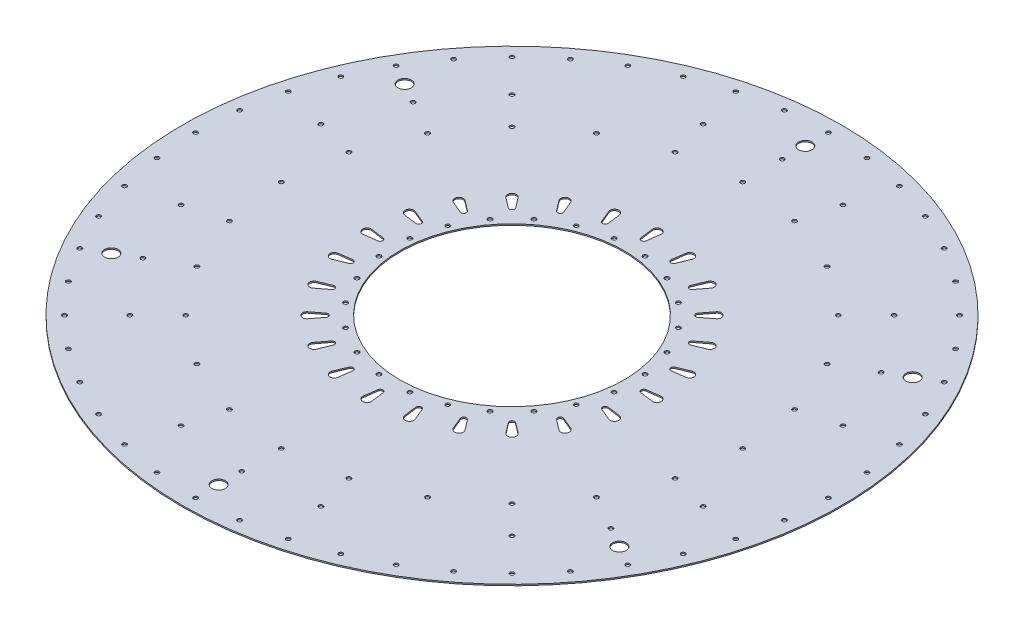
SolidWorks part; units mm, degrees
ref_plane "Front Plane" through (0, 0, 0) normal (0, 0, 1) x (1, 0, 0)
ref_plane "Top Plane" through (0, 0, 0) normal (0, 1, 0) x (1, 0, 0)
ref_plane "Right Plane" through (0, 0, 0) normal (1, 0, 0) x (0, 0, -1)
sketch "Sketch2" plane through (0, 0, 0) normal (0, 1, 0) x (1, 0, 0)
  line L0 (0, 0) -> (0, 231.6511) construction
  line L1 (-5.5, 109.8624) -> (-5, 99.8749) construction
  line L2 (5.5, 109.8624) -> (5, 99.8749) construction
  line L3 (-4.1887, 108.6693) -> (-3.8137, 101.1782) construction
  line L4 (4.1887, 108.6693) -> (3.8137, 101.1782) construction
  line L5 (24.0797, 106.0506) -> (22.5031, 98.7176) construction
  line L6 (32.1717, 103.8824) -> (29.8706, 96.7435) construction
  line L7 (50.7071, 96.2047) -> (47.2863, 89.5297) construction
  line L8 (57.9622, 92.016) -> (53.8918, 85.716) construction
  line L9 (73.8789, 79.8027) -> (68.8471, 74.2404) construction
  line L10 (79.8027, 73.8789) -> (74.2404, 68.8471) construction
  line L11 (92.016, 57.9622) -> (85.716, 53.8918) construction
  line L12 (96.2047, 50.7071) -> (89.5297, 47.2863) construction
  line L13 (103.8824, 32.1717) -> (96.7435, 29.8706) construction
  line L14 (106.0506, 24.0797) -> (98.7176, 22.5031) construction
  line L15 (108.6693, 4.1887) -> (101.1782, 3.8137) construction
  line L16 (108.6693, -4.1887) -> (101.1782, -3.8137) construction
  line L17 (106.0506, -24.0797) -> (98.7176, -22.5031) construction
  line L18 (103.8824, -32.1717) -> (96.7435, -29.8706) construction
  line L19 (96.2047, -50.7071) -> (89.5297, -47.2863) construction
  line L20 (92.016, -57.9622) -> (85.716, -53.8918) construction
  line L21 (79.8027, -73.8789) -> (74.2404, -68.8471) construction
  line L22 (73.8789, -79.8027) -> (68.8471, -74.2404) construction
  line L23 (57.9622, -92.016) -> (53.8918, -85.716) construction
  line L24 (50.7071, -96.2047) -> (47.2863, -89.5297) construction
  line L25 (32.1717, -103.8824) -> (29.8706, -96.7435) construction
  line L26 (24.0797, -106.0506) -> (22.5031, -98.7176) construction
  line L27 (4.1887, -108.6693) -> (3.8137, -101.1782) construction
  line L28 (-4.1887, -108.6693) -> (-3.8137, -101.1782) construction
  line L29 (-24.0797, -106.0506) -> (-22.5031, -98.7176) construction
  line L30 (-32.1717, -103.8824) -> (-29.8706, -96.7435) construction
  line L31 (-50.7071, -96.2047) -> (-47.2863, -89.5297) construction
  line L32 (-57.9622, -92.016) -> (-53.8918, -85.716) construction
  line L33 (-73.8789, -79.8027) -> (-68.8471, -74.2404) construction
  line L34 (-79.8027, -73.8789) -> (-74.2404, -68.8471) construction
  line L35 (-92.016, -57.9622) -> (-85.716, -53.8918) construction
  line L36 (-96.2047, -50.7071) -> (-89.5297, -47.2863) construction
  line L37 (-103.8824, -32.1717) -> (-96.7435, -29.8706) construction
  line L38 (-106.0506, -24.0797) -> (-98.7176, -22.5031) construction
  line L39 (-108.6693, -4.1887) -> (-101.1782, -3.8137) construction
  line L40 (-108.6693, 4.1887) -> (-101.1782, 3.8137) construction
  line L41 (-106.0506, 24.0797) -> (-98.7176, 22.5031) construction
  line L42 (-103.8824, 32.1717) -> (-96.7435, 29.8706) construction
  line L43 (-96.2047, 50.7071) -> (-89.5297, 47.2863) construction
  line L44 (-92.016, 57.9622) -> (-85.716, 53.8918) construction
  line L45 (-79.8027, 73.8789) -> (-74.2404, 68.8471) construction
  line L46 (-73.8789, 79.8027) -> (-68.8471, 74.2404) construction
  line L47 (-57.9622, 92.016) -> (-53.8918, 85.716) construction
  line L48 (-50.7071, 96.2047) -> (-47.2863, 89.5297) construction
  line L49 (-32.1717, 103.8824) -> (-29.8706, 96.7435) construction
  line L50 (-24.0797, 106.0506) -> (-22.5031, 98.7176) construction
  line L51 (0, 0) -> (192.6907, 111.25) construction
  line L52 (3.277, 109.5686) -> (1.9829, 99.7389)
  line L53 (-3.277, 109.5686) -> (-1.9829, 99.7389)
  line L54 (31.5238, 104.987) -> (27.7297, 95.8272)
  line L55 (25.1931, 106.6833) -> (23.899, 96.8536)
  line L56 (57.6222, 93.2507) -> (51.5867, 85.385)
  line L57 (51.9463, 96.5277) -> (48.1522, 87.3679)
  line L58 (79.7939, 75.1595) -> (71.9282, 69.124)
  line L59 (75.1595, 79.7939) -> (69.124, 71.9282)
  line L60 (96.5277, 51.9463) -> (87.3679, 48.1522)
  line L61 (93.2507, 57.6222) -> (85.385, 51.5867)
  line L62 (106.6833, 25.1931) -> (96.8536, 23.899)
  line L63 (104.987, 31.5238) -> (95.8272, 27.7297)
  line L64 (109.5686, -3.277) -> (99.7389, -1.9829)
  line L65 (109.5686, 3.277) -> (99.7389, 1.9829)
  line L66 (104.987, -31.5238) -> (95.8272, -27.7297)
  line L67 (106.6833, -25.1931) -> (96.8536, -23.899)
  line L68 (93.2507, -57.6222) -> (85.385, -51.5867)
  line L69 (96.5277, -51.9463) -> (87.3679, -48.1522)
  line L70 (75.1595, -79.7939) -> (69.124, -71.9282)
  line L71 (79.7939, -75.1595) -> (71.9282, -69.124)
  line L72 (51.9463, -96.5277) -> (48.1522, -87.3679)
  line L73 (57.6222, -93.2507) -> (51.5867, -85.385)
  line L74 (25.1931, -106.6833) -> (23.899, -96.8536)
  line L75 (31.5238, -104.987) -> (27.7297, -95.8272)
  line L76 (-3.277, -109.5686) -> (-1.9829, -99.7389)
  line L77 (3.277, -109.5686) -> (1.9829, -99.7389)
  line L78 (-31.5238, -104.987) -> (-27.7297, -95.8272)
  line L79 (-25.1931, -106.6833) -> (-23.899, -96.8536)
  line L80 (-57.6222, -93.2507) -> (-51.5867, -85.385)
  line L81 (-51.9463, -96.5277) -> (-48.1522, -87.3679)
  line L82 (-79.7939, -75.1595) -> (-71.9282, -69.124)
  line L83 (-75.1595, -79.7939) -> (-69.124, -71.9282)
  line L84 (-96.5277, -51.9463) -> (-87.3679, -48.1522)
  line L85 (-93.2507, -57.6222) -> (-85.385, -51.5867)
  line L86 (-106.6833, -25.1931) -> (-96.8536, -23.899)
  line L87 (-104.987, -31.5238) -> (-95.8272, -27.7297)
  line L88 (-109.5686, 3.277) -> (-99.7389, 1.9829)
  line L89 (-109.5686, -3.277) -> (-99.7389, -1.9829)
  line L90 (-104.987, 31.5238) -> (-95.8272, 27.7297)
  line L91 (-106.6833, 25.1931) -> (-96.8536, 23.899)
  line L92 (-93.2507, 57.6222) -> (-85.385, 51.5867)
  line L93 (-96.5277, 51.9463) -> (-87.3679, 48.1522)
  line L94 (-75.1595, 79.7939) -> (-69.124, 71.9282)
  line L95 (-79.7939, 75.1595) -> (-71.9282, 69.124)
  line L96 (-51.9463, 96.5277) -> (-48.1522, 87.3679)
  line L97 (-57.6222, 93.2507) -> (-51.5867, 85.385)
  line L98 (-25.1931, 106.6833) -> (-23.899, 96.8536)
  line L99 (-31.5238, 104.987) -> (-27.7297, 95.8272)
  line L100 (-175, 0) -> (-175, -31.3263) construction
  line L101 (0, 0) -> (-11.7474, 89.23) construction
  circle A0 centre (0, 0) radius 250
  circle A1 centre (0, 0) radius 145 construction
  arc A2 (5.5, 109.8624) -> (-5.5, 109.8624) centre (0, 0) ccw construction
  arc A3 (5, 99.8749) -> (-5, 99.8749) centre (0, 0) ccw construction
  circle A4 centre (0, 0) radius 95 construction
  arc A5 (-5, 99.8749) -> (5, 99.8749) centre (0, 0) ccw construction
  arc A6 (-5.5, 109.8624) -> (5.5, 109.8624) centre (0, 0) ccw construction
  arc A7 (3.8137, 101.1782) -> (-3.8137, 101.1782) centre (0, 0) ccw construction
  arc A8 (4.1887, 108.6693) -> (-4.1887, 108.6693) centre (0, 0) ccw construction
  arc A9 (29.8706, 96.7435) -> (22.5031, 98.7176) centre (0, 0) ccw construction
  arc A10 (32.1717, 103.8824) -> (24.0797, 106.0506) centre (0, 0) ccw construction
  arc A11 (53.8918, 85.716) -> (47.2863, 89.5297) centre (0, 0) ccw construction
  arc A12 (57.9622, 92.016) -> (50.7071, 96.2047) centre (0, 0) ccw construction
  arc A13 (74.2404, 68.8471) -> (68.8471, 74.2404) centre (0, 0) ccw construction
  arc A14 (79.8027, 73.8789) -> (73.8789, 79.8027) centre (0, 0) ccw construction
  arc A15 (89.5297, 47.2863) -> (85.716, 53.8918) centre (0, 0) ccw construction
  arc A16 (96.2047, 50.7071) -> (92.016, 57.9622) centre (0, 0) ccw construction
  arc A17 (98.7176, 22.5031) -> (96.7435, 29.8706) centre (0, 0) ccw construction
  arc A18 (106.0506, 24.0797) -> (103.8824, 32.1717) centre (0, 0) ccw construction
  arc A19 (101.1782, -3.8137) -> (101.1782, 3.8137) centre (0, 0) ccw construction
  arc A20 (108.6693, -4.1887) -> (108.6693, 4.1887) centre (0, 0) ccw construction
  arc A21 (96.7435, -29.8706) -> (98.7176, -22.5031) centre (0, 0) ccw construction
  arc A22 (103.8824, -32.1717) -> (106.0506, -24.0797) centre (0, 0) ccw construction
  circle A23 centre (0, 240) radius 1.6
  circle A31 centre (0, 0) radius 85
  circle A32 centre (0, 80) radius 1.6
  circle A33 centre (0, 40) radius 1.6 construction
  circle A34 centre (10.3528, 38.637) radius 1.6 construction
  circle A35 centre (20.7055, 77.2741) radius 1.6
  circle A36 centre (20, 34.641) radius 1.6 construction
  circle A37 centre (40, 69.282) radius 1.6
  circle A38 centre (28.2843, 28.2843) radius 1.6 construction
  circle A39 centre (56.5685, 56.5685) radius 1.6
  circle A40 centre (34.641, 20) radius 1.6 construction
  circle A41 centre (69.282, 40) radius 1.6
  circle A42 centre (38.637, 10.3528) radius 1.6 construction
  circle A43 centre (77.2741, 20.7055) radius 1.6
  circle A44 centre (40, 0) radius 1.6 construction
  circle A45 centre (80, 0) radius 1.6
  circle A46 centre (38.637, -10.3528) radius 1.6 construction
  circle A47 centre (77.2741, -20.7055) radius 1.6
  circle A48 centre (231.8222, -62.1166) radius 1.6 [skipped]
  circle A49 centre (62.1166, 231.8222) radius 1.6 [skipped]
  circle A50 centre (120, 207.8461) radius 1.6 [skipped]
  circle A51 centre (240, 0) radius 1.6 [skipped]
  circle A52 centre (231.8222, 62.1166) radius 1.6 [skipped]
  circle A53 centre (169.7056, 169.7056) radius 1.6 [skipped]
  circle A54 centre (207.8461, 120) radius 1.6 [skipped]
  circle A55 centre (31.3263, 237.9468) radius 1.6
  circle A56 centre (62.1166, 231.8222) radius 1.6
  circle A57 centre (91.844, 221.7311) radius 1.6
  circle A58 centre (120, 207.8461) radius 1.6
  circle A59 centre (146.1027, 190.4048) radius 1.6
  arc A60 (85.716, -53.8918) -> (89.5297, -47.2863) centre (0, 0) ccw construction
  arc A61 (92.016, -57.9622) -> (96.2047, -50.7071) centre (0, 0) ccw construction
  circle A62 centre (207.8461, -120) radius 1.6
  circle A63 centre (34.641, -20) radius 1.6 construction
  circle A64 centre (69.282, -40) radius 1.6
  arc A65 (68.8471, -74.2404) -> (74.2404, -68.8471) centre (0, 0) ccw construction
  arc A66 (73.8789, -79.8027) -> (79.8027, -73.8789) centre (0, 0) ccw construction
  circle A67 centre (169.7056, -169.7056) radius 1.6
  circle A68 centre (28.2843, -28.2843) radius 1.6 construction
  circle A69 centre (56.5685, -56.5685) radius 1.6
  arc A70 (47.2863, -89.5297) -> (53.8918, -85.716) centre (0, 0) ccw construction
  arc A71 (50.7071, -96.2047) -> (57.9622, -92.016) centre (0, 0) ccw construction
  circle A72 centre (120, -207.8461) radius 1.6
  circle A73 centre (20, -34.641) radius 1.6 construction
  circle A74 centre (40, -69.282) radius 1.6
  arc A75 (22.5031, -98.7176) -> (29.8706, -96.7435) centre (0, 0) ccw construction
  arc A76 (24.0797, -106.0506) -> (32.1717, -103.8824) centre (0, 0) ccw construction
  circle A77 centre (62.1166, -231.8222) radius 1.6
  circle A78 centre (10.3528, -38.637) radius 1.6 construction
  circle A79 centre (20.7055, -77.2741) radius 1.6
  arc A80 (-3.8137, -101.1782) -> (3.8137, -101.1782) centre (0, 0) ccw construction
  arc A81 (-4.1887, -108.6693) -> (4.1887, -108.6693) centre (0, 0) ccw construction
  circle A82 centre (0, -240) radius 1.6
  circle A83 centre (0, -40) radius 1.6 construction
  circle A84 centre (0, -80) radius 1.6
  arc A85 (-29.8706, -96.7435) -> (-22.5031, -98.7176) centre (0, 0) ccw construction
  arc A86 (-32.1717, -103.8824) -> (-24.0797, -106.0506) centre (0, 0) ccw construction
  circle A87 centre (-62.1166, -231.8222) radius 1.6
  circle A88 centre (-10.3528, -38.637) radius 1.6 construction
  circle A89 centre (-20.7055, -77.2741) radius 1.6
  arc A90 (-53.8918, -85.716) -> (-47.2863, -89.5297) centre (0, 0) ccw construction
  arc A91 (-57.9622, -92.016) -> (-50.7071, -96.2047) centre (0, 0) ccw construction
  circle A92 centre (-120, -207.8461) radius 1.6
  circle A93 centre (-20, -34.641) radius 1.6 construction
  circle A94 centre (-40, -69.282) radius 1.6
  arc A95 (-74.2404, -68.8471) -> (-68.8471, -74.2404) centre (0, 0) ccw construction
  arc A96 (-79.8027, -73.8789) -> (-73.8789, -79.8027) centre (0, 0) ccw construction
  circle A97 centre (-169.7056, -169.7056) radius 1.6
  circle A98 centre (-28.2843, -28.2843) radius 1.6 construction
  circle A99 centre (-56.5685, -56.5685) radius 1.6
  arc A100 (-89.5297, -47.2863) -> (-85.716, -53.8918) centre (0, 0) ccw construction
  arc A101 (-96.2047, -50.7071) -> (-92.016, -57.9622) centre (0, 0) ccw construction
  circle A102 centre (-207.8461, -120) radius 1.6
  circle A103 centre (-34.641, -20) radius 1.6 construction
  circle A104 centre (-69.282, -40) radius 1.6
  arc A105 (-98.7176, -22.5031) -> (-96.7435, -29.8706) centre (0, 0) ccw construction
  arc A106 (-106.0506, -24.0797) -> (-103.8824, -32.1717) centre (0, 0) ccw construction
  circle A107 centre (-231.8222, -62.1166) radius 1.6
  circle A108 centre (-38.637, -10.3528) radius 1.6 construction
  circle A109 centre (-77.2741, -20.7055) radius 1.6
  arc A110 (-101.1782, 3.8137) -> (-101.1782, -3.8137) centre (0, 0) ccw construction
  arc A111 (-108.6693, 4.1887) -> (-108.6693, -4.1887) centre (0, 0) ccw construction
  circle A112 centre (-240, 0) radius 1.6
  circle A113 centre (-40, 0) radius 1.6 construction
  circle A114 centre (-80, 0) radius 1.6
  arc A115 (-96.7435, 29.8706) -> (-98.7176, 22.5031) centre (0, 0) ccw construction
  arc A116 (-103.8824, 32.1717) -> (-106.0506, 24.0797) centre (0, 0) ccw construction
  circle A117 centre (-231.8222, 62.1166) radius 1.6
  circle A118 centre (-38.637, 10.3528) radius 1.6 construction
  circle A119 centre (-77.2741, 20.7055) radius 1.6
  arc A120 (-85.716, 53.8918) -> (-89.5297, 47.2863) centre (0, 0) ccw construction
  arc A121 (-92.016, 57.9622) -> (-96.2047, 50.7071) centre (0, 0) ccw construction
  circle A122 centre (-207.8461, 120) radius 1.6
  circle A123 centre (-34.641, 20) radius 1.6 construction
  circle A124 centre (-69.282, 40) radius 1.6
  arc A125 (-68.8471, 74.2404) -> (-74.2404, 68.8471) centre (0, 0) ccw construction
  arc A126 (-73.8789, 79.8027) -> (-79.8027, 73.8789) centre (0, 0) ccw construction
  circle A127 centre (-169.7056, 169.7056) radius 1.6
  circle A128 centre (-28.2843, 28.2843) radius 1.6 construction
  circle A129 centre (-56.5685, 56.5685) radius 1.6
  arc A130 (-47.2863, 89.5297) -> (-53.8918, 85.716) centre (0, 0) ccw construction
  arc A131 (-50.7071, 96.2047) -> (-57.9622, 92.016) centre (0, 0) ccw construction
  circle A132 centre (-120, 207.8461) radius 1.6
  circle A133 centre (-20, 34.641) radius 1.6 construction
  circle A134 centre (-40, 69.282) radius 1.6
  arc A135 (-22.5031, 98.7176) -> (-29.8706, 96.7435) centre (0, 0) ccw construction
  arc A136 (-24.0797, 106.0506) -> (-32.1717, 103.8824) centre (0, 0) ccw construction
  circle A137 centre (-62.1166, 231.8222) radius 1.6
  circle A138 centre (-10.3528, 38.637) radius 1.6 construction
  circle A139 centre (-20.7055, 77.2741) radius 1.6
  circle A140 centre (169.7056, 169.7056) radius 1.6
  circle A141 centre (190.4048, 146.1027) radius 1.6
  circle A142 centre (207.8461, 120) radius 1.6
  circle A143 centre (221.7311, 91.844) radius 1.6
  circle A144 centre (231.8222, 62.1166) radius 1.6
  circle A145 centre (237.9468, 31.3263) radius 1.6
  circle A146 centre (240, 0) radius 1.6
  circle A147 centre (237.9468, -31.3263) radius 1.6
  circle A148 centre (231.8222, -62.1166) radius 1.6
  circle A149 centre (221.7311, -91.844) radius 1.6
  circle A150 centre (207.8461, -120) radius 1.6
  circle A151 centre (190.4048, -146.1027) radius 1.6
  circle A152 centre (169.7056, -169.7056) radius 1.6
  circle A153 centre (146.1027, -190.4048) radius 1.6
  circle A154 centre (120, -207.8461) radius 1.6
  circle A155 centre (91.844, -221.7311) radius 1.6
  circle A156 centre (62.1166, -231.8222) radius 1.6
  circle A157 centre (31.3263, -237.9468) radius 1.6
  circle A158 centre (0, -240) radius 1.6
  circle A159 centre (-31.3263, -237.9468) radius 1.6
  circle A160 centre (-62.1166, -231.8222) radius 1.6
  circle A161 centre (-91.844, -221.7311) radius 1.6
  circle A162 centre (-120, -207.8461) radius 1.6
  circle A163 centre (-146.1027, -190.4048) radius 1.6
  circle A164 centre (-169.7056, -169.7056) radius 1.6
  circle A165 centre (-190.4048, -146.1027) radius 1.6
  circle A166 centre (-207.8461, -120) radius 1.6
  circle A167 centre (-221.7311, -91.844) radius 1.6
  circle A168 centre (-231.8222, -62.1166) radius 1.6
  circle A169 centre (-237.9468, -31.3263) radius 1.6
  circle A170 centre (-240, 0) radius 1.6
  circle A171 centre (-237.9468, 31.3263) radius 1.6
  circle A172 centre (-231.8222, 62.1166) radius 1.6
  circle A173 centre (-221.7311, 91.844) radius 1.6
  circle A174 centre (-207.8461, 120) radius 1.6
  circle A175 centre (-190.4048, 146.1027) radius 1.6
  circle A176 centre (-169.7056, 169.7056) radius 1.6
  circle A177 centre (-146.1027, 190.4048) radius 1.6
  circle A178 centre (-120, 207.8461) radius 1.6
  circle A179 centre (-91.844, 221.7311) radius 1.6
  circle A180 centre (-62.1166, 231.8222) radius 1.6
  circle A181 centre (-31.3263, 237.9468) radius 1.6
  circle A182 centre (0, 0) radius 222.5 construction
  circle A183 centre (0, 222.5) radius 5.1
  circle A184 centre (192.6907, 111.25) radius 5.1
  circle A185 centre (192.6907, -111.25) radius 5.1
  circle A186 centre (0, -222.5) radius 5.1
  circle A187 centre (-192.6907, -111.25) radius 5.1
  circle A188 centre (-192.6907, 111.25) radius 5.1
  circle A189 centre (0, 0) radius 175 construction
  circle A190 centre (0, 175) radius 1.6
  circle A191 centre (45.2933, 169.037) radius 1.6
  circle A192 centre (87.5, 151.5544) radius 1.6
  circle A193 centre (123.7437, 123.7437) radius 1.6
  circle A194 centre (151.5544, 87.5) radius 1.6
  circle A195 centre (169.037, 45.2933) radius 1.6
  circle A196 centre (175, 0) radius 1.6
  circle A197 centre (169.037, -45.2933) radius 1.6
  circle A198 centre (151.5544, -87.5) radius 1.6
  circle A199 centre (123.7437, -123.7437) radius 1.6
  circle A200 centre (87.5, -151.5544) radius 1.6
  circle A201 centre (45.2933, -169.037) radius 1.6
  circle A202 centre (0, -175) radius 1.6
  circle A203 centre (-45.2933, -169.037) radius 1.6
  circle A204 centre (-87.5, -151.5544) radius 1.6
  circle A205 centre (-123.7437, -123.7437) radius 1.6
  circle A206 centre (-151.5544, -87.5) radius 1.6
  circle A207 centre (-169.037, -45.2933) radius 1.6
  circle A208 centre (-175, 0) radius 1.6
  circle A209 centre (-169.037, 45.2933) radius 1.6
  circle A210 centre (-151.5544, 87.5) radius 1.6
  circle A211 centre (-123.7437, 123.7437) radius 1.6
  circle A212 centre (-87.5, 151.5544) radius 1.6
  circle A213 centre (-45.2933, 169.037) radius 1.6
  arc A214 (-1.9829, 99.7389) -> (1.9829, 99.7389) centre (0, 100) ccw
  arc A215 (3.277, 109.5686) -> (-3.277, 109.5686) centre (0, 110) ccw
  arc A216 (23.899, 96.8536) -> (27.7297, 95.8272) centre (25.8819, 96.5926) ccw
  arc A217 (31.5238, 104.987) -> (25.1931, 106.6833) centre (28.4701, 106.2518) ccw
  arc A218 (48.1522, 87.3679) -> (51.5867, 85.385) centre (50, 86.6025) ccw
  arc A219 (57.6222, 93.2507) -> (51.9463, 96.5277) centre (55, 95.2628) ccw
  arc A220 (69.124, 71.9282) -> (71.9282, 69.124) centre (70.7107, 70.7107) ccw
  arc A221 (79.7939, 75.1595) -> (75.1595, 79.7939) centre (77.7817, 77.7817) ccw
  arc A222 (85.385, 51.5867) -> (87.3679, 48.1522) centre (86.6025, 50) ccw
  arc A223 (96.5277, 51.9463) -> (93.2507, 57.6222) centre (95.2628, 55) ccw
  arc A224 (95.8272, 27.7297) -> (96.8536, 23.899) centre (96.5926, 25.8819) ccw
  arc A225 (106.6833, 25.1931) -> (104.987, 31.5238) centre (106.2518, 28.4701) ccw
  arc A226 (99.7389, 1.9829) -> (99.7389, -1.9829) centre (100, 0) ccw
  arc A227 (109.5686, -3.277) -> (109.5686, 3.277) centre (110, 0) ccw
  arc A228 (96.8536, -23.899) -> (95.8272, -27.7297) centre (96.5926, -25.8819) ccw
  arc A229 (104.987, -31.5238) -> (106.6833, -25.1931) centre (106.2518, -28.4701) ccw
  arc A230 (87.3679, -48.1522) -> (85.385, -51.5867) centre (86.6025, -50) ccw
  arc A231 (93.2507, -57.6222) -> (96.5277, -51.9463) centre (95.2628, -55) ccw
  arc A232 (71.9282, -69.124) -> (69.124, -71.9282) centre (70.7107, -70.7107) ccw
  arc A233 (75.1595, -79.7939) -> (79.7939, -75.1595) centre (77.7817, -77.7817) ccw
  arc A234 (51.5867, -85.385) -> (48.1522, -87.3679) centre (50, -86.6025) ccw
  arc A235 (51.9463, -96.5277) -> (57.6222, -93.2507) centre (55, -95.2628) ccw
  arc A236 (27.7297, -95.8272) -> (23.899, -96.8536) centre (25.8819, -96.5926) ccw
  arc A237 (25.1931, -106.6833) -> (31.5238, -104.987) centre (28.4701, -106.2518) ccw
  arc A238 (1.9829, -99.7389) -> (-1.9829, -99.7389) centre (0, -100) ccw
  arc A239 (-3.277, -109.5686) -> (3.277, -109.5686) centre (0, -110) ccw
  arc A240 (-23.899, -96.8536) -> (-27.7297, -95.8272) centre (-25.8819, -96.5926) ccw
  arc A241 (-31.5238, -104.987) -> (-25.1931, -106.6833) centre (-28.4701, -106.2518) ccw
  arc A242 (-48.1522, -87.3679) -> (-51.5867, -85.385) centre (-50, -86.6025) ccw
  arc A243 (-57.6222, -93.2507) -> (-51.9463, -96.5277) centre (-55, -95.2628) ccw
  arc A244 (-69.124, -71.9282) -> (-71.9282, -69.124) centre (-70.7107, -70.7107) ccw
  arc A245 (-79.7939, -75.1595) -> (-75.1595, -79.7939) centre (-77.7817, -77.7817) ccw
  arc A246 (-85.385, -51.5867) -> (-87.3679, -48.1522) centre (-86.6025, -50) ccw
  arc A247 (-96.5277, -51.9463) -> (-93.2507, -57.6222) centre (-95.2628, -55) ccw
  arc A248 (-95.8272, -27.7297) -> (-96.8536, -23.899) centre (-96.5926, -25.8819) ccw
  arc A249 (-106.6833, -25.1931) -> (-104.987, -31.5238) centre (-106.2518, -28.4701) ccw
  arc A250 (-99.7389, -1.9829) -> (-99.7389, 1.9829) centre (-100, 0) ccw
  arc A251 (-109.5686, 3.277) -> (-109.5686, -3.277) centre (-110, 0) ccw
  arc A252 (-96.8536, 23.899) -> (-95.8272, 27.7297) centre (-96.5926, 25.8819) ccw
  arc A253 (-104.987, 31.5238) -> (-106.6833, 25.1931) centre (-106.2518, 28.4701) ccw
  arc A254 (-87.3679, 48.1522) -> (-85.385, 51.5867) centre (-86.6025, 50) ccw
  arc A255 (-93.2507, 57.6222) -> (-96.5277, 51.9463) centre (-95.2628, 55) ccw
  arc A256 (-71.9282, 69.124) -> (-69.124, 71.9282) centre (-70.7107, 70.7107) ccw
  arc A257 (-75.1595, 79.7939) -> (-79.7939, 75.1595) centre (-77.7817, 77.7817) ccw
  arc A258 (-51.5867, 85.385) -> (-48.1522, 87.3679) centre (-50, 86.6025) ccw
  arc A259 (-51.9463, 96.5277) -> (-57.6222, 93.2507) centre (-55, 95.2628) ccw
  arc A260 (-27.7297, 95.8272) -> (-23.899, 96.8536) centre (-25.8819, 96.5926) ccw
  arc A261 (-25.1931, 106.6833) -> (-31.5238, 104.987) centre (-28.4701, 106.2518) ccw
  circle A262 centre (-145, 0) radius 1.6 construction
  circle A263 centre (-205, 0) radius 1.6 construction
  circle A264 centre (-198.0148, 53.0579) radius 1.6
  circle A265 centre (-177.5352, 102.5) radius 1.6
  circle A266 centre (-144.9569, 144.9569) radius 1.6
  circle A267 centre (-102.5, 177.5352) radius 1.6 construction
  circle A268 centre (-53.0579, 198.0148) radius 1.6
  circle A269 centre (0, 205) radius 1.6
  circle A270 centre (53.0579, 198.0148) radius 1.6
  circle A271 centre (102.5, 177.5352) radius 1.6 construction
  circle A272 centre (144.9569, 144.9569) radius 1.6
  circle A273 centre (177.5352, 102.5) radius 1.6
  circle A274 centre (198.0148, 53.0579) radius 1.6
  circle A275 centre (205, 0) radius 1.6 construction
  circle A276 centre (198.0148, -53.0579) radius 1.6
  circle A277 centre (177.5352, -102.5) radius 1.6
  circle A278 centre (144.9569, -144.9569) radius 1.6
  circle A279 centre (102.5, -177.5352) radius 1.6 construction
  circle A280 centre (53.0579, -198.0148) radius 1.6
  circle A281 centre (0, -205) radius 1.6
  circle A282 centre (-53.0579, -198.0148) radius 1.6
  circle A283 centre (-102.5, -177.5352) radius 1.6 construction
  circle A284 centre (-144.9569, -144.9569) radius 1.6
  circle A285 centre (-177.5352, -102.5) radius 1.6
  circle A286 centre (-198.0148, -53.0579) radius 1.6
  circle A287 centre (-140.0592, 37.5288) radius 1.6 construction
  circle A288 centre (-125.5737, 72.5) radius 1.6 construction
  circle A289 centre (-102.5305, 102.5305) radius 1.6 construction
  circle A290 centre (-72.5, 125.5737) radius 1.6 construction
  circle A291 centre (-37.5288, 140.0592) radius 1.6 construction
  circle A292 centre (0, 145) radius 1.6 construction
  circle A293 centre (37.5288, 140.0592) radius 1.6 construction
  circle A294 centre (72.5, 125.5737) radius 1.6 construction
  circle A295 centre (102.5305, 102.5305) radius 1.6 construction
  circle A296 centre (125.5737, 72.5) radius 1.6 construction
  circle A297 centre (140.0592, 37.5288) radius 1.6 construction
  circle A298 centre (145, 0) radius 1.6 construction
  circle A299 centre (140.0592, -37.5288) radius 1.6 construction
  circle A300 centre (125.5737, -72.5) radius 1.6 construction
  circle A301 centre (102.5305, -102.5305) radius 1.6 construction
  circle A302 centre (72.5, -125.5737) radius 1.6 construction
  circle A303 centre (37.5288, -140.0592) radius 1.6 construction
  circle A304 centre (0, -145) radius 1.6 construction
  circle A305 centre (-37.5288, -140.0592) radius 1.6 construction
  circle A306 centre (-72.5, -125.5737) radius 1.6 construction
  circle A307 centre (-102.5305, -102.5305) radius 1.6 construction
  circle A308 centre (-125.5737, -72.5) radius 1.6 construction
  circle A309 centre (-140.0592, -37.5288) radius 1.6 construction
  circle A310 centre (-11.7474, 89.23) radius 1.6
  circle A311 centre (11.7474, 89.23) radius 1.6
  circle A312 centre (34.4415, 83.1492) radius 1.6
  circle A313 centre (54.7885, 71.4018) radius 1.6
  circle A314 centre (71.4018, 54.7885) radius 1.6
  circle A315 centre (83.1492, 34.4415) radius 1.6
  circle A316 centre (89.23, 11.7474) radius 1.6
  circle A317 centre (89.23, -11.7474) radius 1.6
  circle A318 centre (83.1492, -34.4415) radius 1.6
  circle A319 centre (71.4018, -54.7885) radius 1.6
  circle A320 centre (54.7885, -71.4018) radius 1.6
  circle A321 centre (34.4415, -83.1492) radius 1.6
  circle A322 centre (11.7474, -89.23) radius 1.6
  circle A323 centre (-11.7474, -89.23) radius 1.6
  circle A324 centre (-34.4415, -83.1492) radius 1.6
  circle A325 centre (-54.7885, -71.4018) radius 1.6
  circle A326 centre (-71.4018, -54.7885) radius 1.6
  circle A327 centre (-83.1492, -34.4415) radius 1.6
  circle A328 centre (-89.23, -11.7474) radius 1.6
  circle A329 centre (-89.23, 11.7474) radius 1.6
  circle A330 centre (-83.1492, 34.4415) radius 1.6
  circle A331 centre (-71.4018, 54.7885) radius 1.6
  circle A332 centre (-54.7885, 71.4018) radius 1.6
  circle A333 centre (-34.4415, 83.1492) radius 1.6
  point P46 (0, 0)
  point P62 (0, 0)
  point P364 (0, 0)
  point P415 (0, 0)
  point P560 (0, 0)
  point P612 (0, 0)
  point P659 (0, 0)
  point P708 (0, 0)
  dimension "D1" = 500
  dimension "D2" = 290
  dimension "D3" = 220
  dimension "D4" = 200
  dimension "D5" = 190
  dimension "D9" = 3.2
  dimension "D11" = 170
  dimension "D12" = 40
  dimension "D14" = 3.2
  dimension "D16" = 445
  dimension "D17" = 10.2
  dimension "D20" = 350
  dimension "D21" = 3.2
  dimension "D26" = 90
  dimension "D27" = 7.5
  dimension "D28" = 3.2
  dimension "D6" = 10
  dimension "D7" = 1.25
  dimension "D10" = 240
  dimension "D13" = 40
  dimension "D15" = 48
  dimension "D19" = 60
  dimension "D24" = 24
  dimension "D8" = 24
  dimension "D18" = 6
  dimension "D22" = 24
  dimension "D23" = 24
  dimension "D25" = 24
  dimension "D29" = 24
extrude "Boss-Extrude1" add sketch "Sketch2" along normal mid plane 1 contours A0 A137 A136 L50 A135 L49 A132 A131 L48 A130 L47 A127 A126 L46 A125 L45 A121 L44 A120 L43 A117 A116 L42 A115 L41 A112 A111 L40 A110 L39 A107 A106 L38 A105 L37 A101 L36
